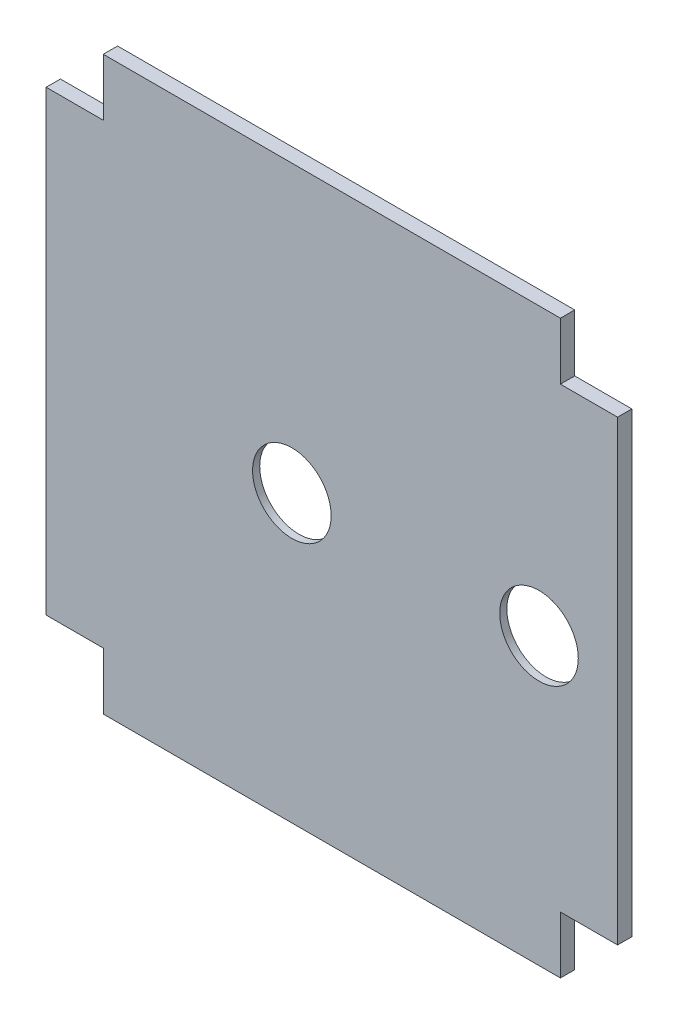
SolidWorks part; units mm, degrees
ref_plane "Front Plane" through (0, 0, 0) normal (0, 0, 1) x (1, 0, 0)
ref_plane "Top Plane" through (0, 0, 0) normal (0, 1, 0) x (1, 0, 0)
ref_plane "Right Plane" through (0, 0, 0) normal (1, 0, 0) x (0, 0, -1)
sketch "Sketch1" plane through (0, 0, 0) normal (0, 0, 1) x (1, 0, 0)
  line L1 (0, 0) -> (400, 0)
  line L2 (0, 0) -> (0, 400)
  line L3 (0, 400) -> (400, 400)
  line L4 (400, 0) -> (400, 400)
  dimension "D1" = 400
  dimension "D2" = 400
extrude "Boss-Extrude1" add sketch "Sketch1" along normal blind 10 contours L3 L4 L1 L2
sketch "Sketch2" plane through (0, 0, 10) normal (0, 0, 1) x (1, 0, 0)
  line L5 (0, 200) -> (50, 200) construction
  line L6 (0, 0) -> (0, 400) construction
  circle A1 centre (55, 200) radius 5
  dimension "D3" = 10
  dimension "D4" = 50
sketch "Sketch4" plane through (0, 0, 10) normal (0, 0, 1) x (1, 0, 0)
  line L0 (400, 200) -> (372.5001, 200) construction
  line L1 (400, 0) -> (400, 400) construction
  line L2 (345.0002, 199.9663) -> (172.0002, 199.9663) construction
  circle A0 centre (345.0002, 199.9663) radius 27.5
  circle A1 centre (172.0002, 199.9663) radius 27.5
  point P7 (400, 200)
  dimension "D2" = 55
  dimension "D3" = 173
  dimension "D1" = 54.9998
extrude "Cut-Extrude2" cut sketch "Sketch4" against normal through all
sketch "Sketch5" plane through (0, 0, 0) normal (0, 0, -1) x (-1, 0, 0)
  circle A0 centre (-345.0002, 199.9663) radius 35
  circle A1 centre (-172.0002, 199.9663) radius 35
  dimension "D1" = 70
  dimension "D2" = 70
extrude "Cut-Extrude3" cut sketch "Sketch5" against normal blind 5
sketch "Sketch6" plane through (0, 0, 0) normal (0, 0, -1) x (-1, 0, 0)
  line L1 (-400, 400) -> (-360, 400)
  line L2 (-400, 400) -> (-400, 360)
  line L3 (-400, 360) -> (-360, 360)
  line L4 (-360, 400) -> (-360, 360)
  line L5 (-400, 0) -> (-360, 0)
  line L6 (-400, 0) -> (-400, 40)
  line L7 (-400, 40) -> (-360, 40)
  line L8 (-360, 0) -> (-360, 40)
  line L9 (0, 400) -> (-40, 400)
  line L10 (0, 400) -> (0, 360)
  line L11 (0, 360) -> (-40, 360)
  line L12 (-40, 400) -> (-40, 360)
  line L13 (0, 0) -> (-40, 0)
  line L14 (0, 0) -> (0, 40)
  line L15 (0, 40) -> (-40, 40)
  line L16 (-40, 0) -> (-40, 40)
  dimension "D1" = 40
extrude "Cut-Extrude4" cut sketch "Sketch6" against normal through all
